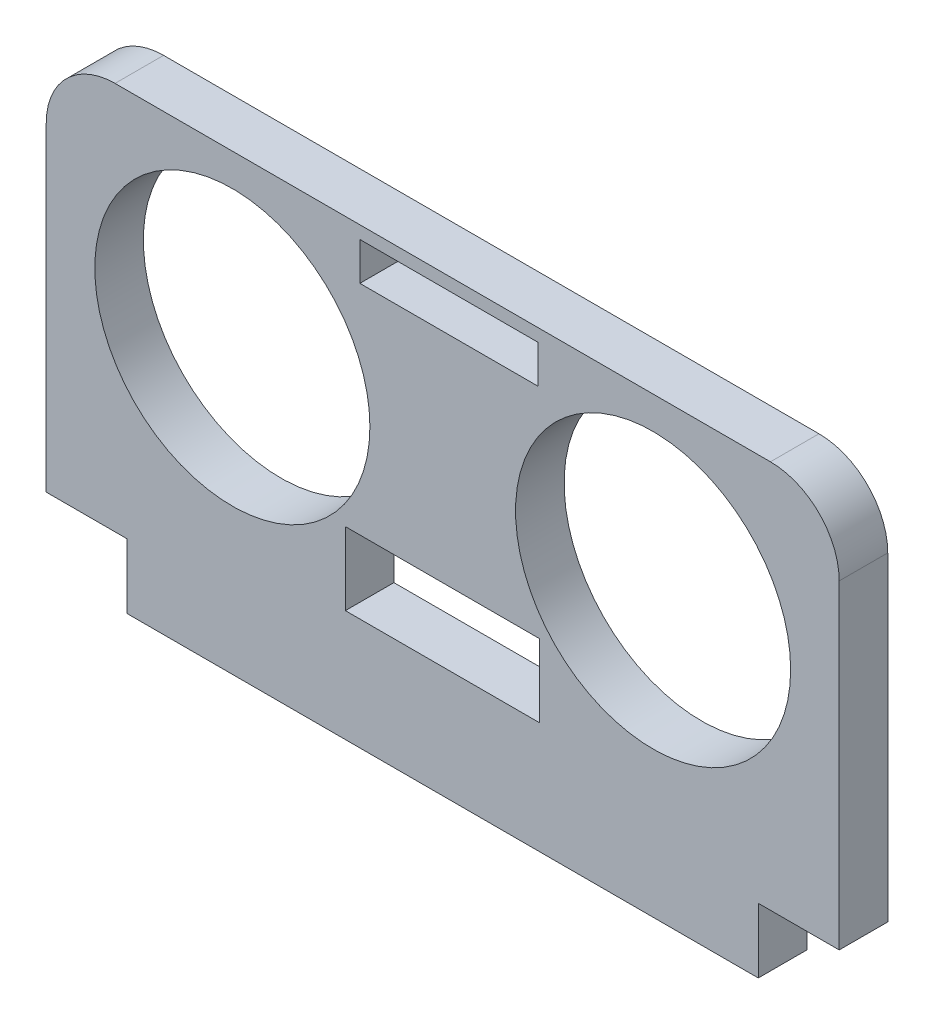
SolidWorks part; units mm, degrees
material "Oak"
ref_plane "Front" through (0, 0, 0) normal (0, 0, 1) x (1, 0, 0)
ref_plane "Top" through (0, 0, 0) normal (0, 1, 0) x (1, 0, 0)
ref_plane "Right" through (0, 0, 0) normal (1, 0, 0) x (0, 0, -1)
sketch "Sketch1" plane through (0, 0, 0) normal (0, 0, 1) x (1, 0, 0)
  line L0 (-67.7235, 14.6917) -> (-67.7235, -5.0583)
  line L1 (-49.2403, 2.3419) -> (-37.2403, 2.3419)
  line L2 (-49.2403, 2.3419) -> (-49.2403, -2.1581)
  line L3 (-49.2403, -2.1581) -> (-37.2403, -2.1581)
  line L4 (-37.2403, 2.3419) -> (-37.2403, -2.1581)
  line L5 (-48.3445, 18.1549) -> (-37.3445, 18.1549)
  line L6 (-48.3445, 18.1549) -> (-48.3445, 15.8049)
  line L7 (-48.3445, 15.8049) -> (-37.3445, 15.8049)
  line L8 (-37.3445, 18.1549) -> (-37.3445, 15.8049)
  line L9 (-67.7235, -5.0583) -> (-62.7235, -5.0583)
  line L10 (-62.7235, -5.0583) -> (-62.7235, -9.0583)
  line L11 (-22.9735, 18.9417) -> (-63.4735, 18.9417)
  line L12 (-18.7235, -5.0583) -> (-23.7235, -5.0583)
  line L13 (-23.7235, -5.0583) -> (-23.7235, -9.0583)
  line L14 (-62.7235, -9.0583) -> (-23.7235, -9.0583)
  line L21 (-18.7235, -5.0583) -> (-18.7235, 14.6917)
  circle A0 centre (-56.2235, 8.4417) radius 8.5
  circle A2 centre (-30.2235, 8.4417) radius 8.5
  arc A3 (-22.9735, 18.9417) -> (-18.7235, 14.6917) centre (-22.9735, 14.6917) cw
  arc A4 (-63.4735, 18.9417) -> (-67.7235, 14.6917) centre (-63.4735, 14.6917) ccw
  dimension "D1" = 4.25
  dimension "D2" = 4.25
extrude "Boss-Extrude2" add sketch "Sketch1" along normal blind 3
